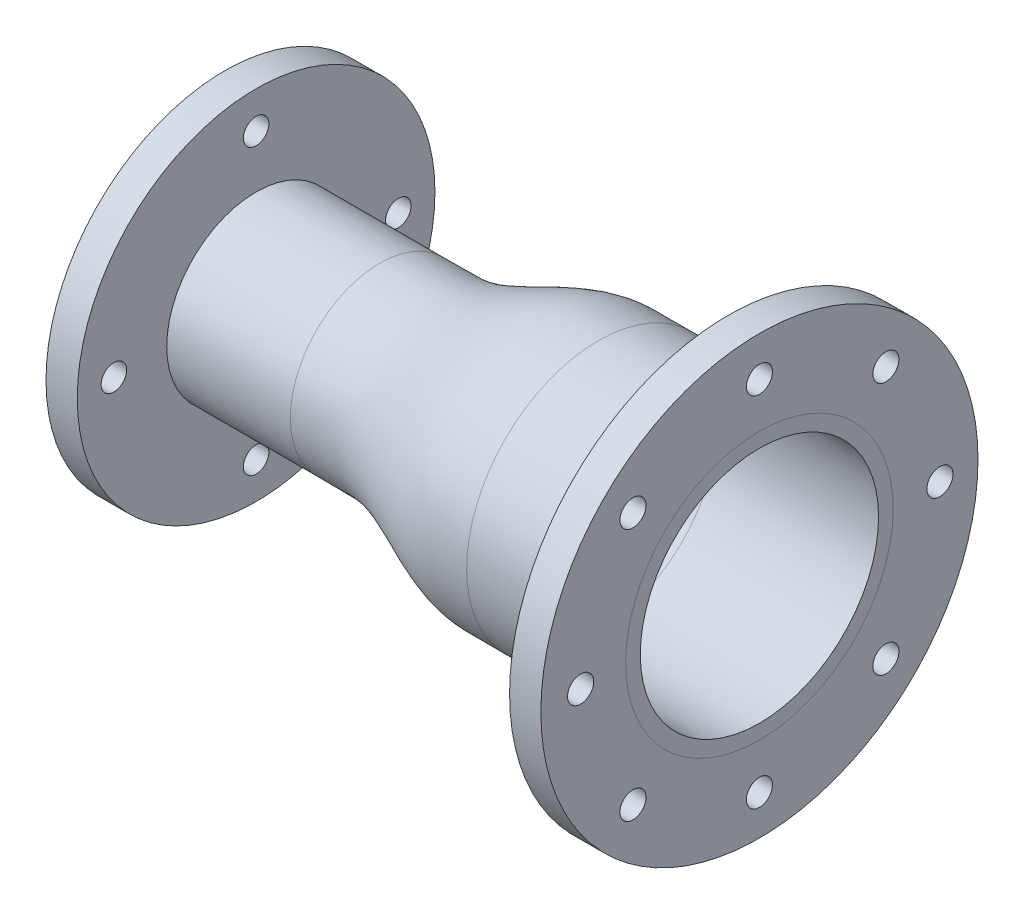
SolidWorks part; units mm, degrees
material "Cast Alloy Steel"
ref_plane "Front Plane" through (0, 0, 0) normal (0, 0, 1) x (1, 0, 0)
ref_plane "Top Plane" through (0, 0, 0) normal (0, 1, 0) x (1, 0, 0)
ref_plane "Right Plane" through (0, 0, 0) normal (1, 0, 0) x (0, 0, -1)
other "Configuration Table"
sketch "Sketch2" plane through (0, 0, 0) normal (0, 0, 1) x (1, 0, 0)
  line L0 (341.7, 0) -> (0, 0) construction
  line L4 (341.7, 76.1375) -> (341.7, 139.7)
  line L5 (20, 114.3) -> (0, 114.3)
  line L6 (341.7, 139.7) -> (321.7, 139.7)
  line L8 (0, 114.3) -> (0, 49.15)
  line L9 (321.7, 139.7) -> (321.7, 84.1375)
  line L10 (20, 114.3) -> (20, 57.15)
  line L11 (99, 57.15) -> (20, 57.15)
  line L12 (238.7, 76.1375) -> (321.7, 76.1375) construction
  line L13 (238.7, 84.1375) -> (321.7, 84.1375)
  line L14 (238.7, 76.1375) -> (341.7, 76.1375)
  line L15 (99, 49.15) -> (0, 49.15)
  line L16 (99, 49.15) -> (20, 49.15) construction
  spline S1 degree 3 poles (238.7, 84.1375) (238.3559, 84.1375) (237.6678, 84.1375) (236.4389, 84.1375) (234.866, 84.1375) (233.0965, 84.1375) (231.1795, 84.1375) (229.4099, 84.1375) (227.493, 84.1375) (225.7234, 84.1375) (223.8064, 84.1375) (222.0369, 84.1375) (220.1199, 84.1374) (218.3504, 84.1379) (216.4362, 84.1363) (214.6713, 84.1428) (212.7611, 84.0867) (210.998, 83.9819) (209.0881, 83.8116) (207.3251, 83.6037) (205.4153, 83.3256) (203.6525, 83.0215) (201.743, 82.6431) (199.9803, 82.2501) (198.071, 81.7796) (196.3085, 81.3056) (194.3993, 80.7519) (192.637, 80.2054) (190.7279, 79.5779) (188.9657, 78.9679) (187.0568, 78.2765) (185.2947, 77.6123) (183.3858, 76.8675) (181.6238, 76.159) (179.715, 75.3717) (177.9531, 74.629) (176.0443, 73.8103) (174.2824, 73.0438) (172.3737, 72.2052) (170.6119, 71.4256) (168.7018, 70.578) (166.9374, 69.795) (165.0248, 68.9495) (163.2593, 68.1744) (161.3467, 67.3439) (159.5811, 66.588) (157.6684, 65.784) (155.9029, 65.0579) (153.9901, 64.2918) (152.2245, 63.6059) (150.3116, 62.8888) (148.5459, 62.253) (146.6329, 61.5955) (144.8671, 61.0196) (142.954, 60.432) (141.188, 59.9252) (139.2748, 59.4172) (137.5086, 58.9881) (135.5952, 58.5689) (133.8288, 58.2258) (131.9153, 57.9039) (130.1487, 57.6544) (128.235, 57.4377) (126.4683, 57.2886) (124.7896, 57.1975) (123.4438, 57.157) (122.4205, 57.149) (121.678, 57.1501) (120.6018, 57.1498) (119.2022, 57.15) (117.2852, 57.15) (115.5156, 57.15) (113.5986, 57.15) (111.8291, 57.15) (109.9121, 57.15) (108.1426, 57.15) (106.2256, 57.15) (104.4561, 57.15) (102.5391, 57.15) (101.0399, 57.15) (99.811, 57.15) (99.2703, 57.15) (99, 57.15) knots 0 0 0 0 0.007154 0.014308 0.025551 0.039859 0.051101 0.06541 0.076652 0.09096 0.102202 0.116511 0.127753 0.142061 0.153304 0.167554 0.178755 0.193031 0.204272 0.218621 0.229935 0.244395 0.25581 0.270409 0.28194 0.296695 0.308353 0.323271 0.335057 0.350135 0.362043 0.377271 0.389288 0.404646 0.416757 0.43222 0.444402 0.459941 0.47217 0.487751 0.5 0.515621 0.527887 0.54348 0.555711 0.571243 0.583412 0.598851 0.610936 0.626254 0.638235 0.65341 0.665273 0.680292 0.692028 0.706883 0.718491 0.733185 0.74467 0.759216 0.770593 0.785014 0.796305 0.810635 0.821871 0.831257 0.838628 0.843146 0.846696 0.861005 0.872247 0.886555 0.897798 0.912106 0.923348 0.937657 0.948899 0.963207 0.974449 0.988758 0.994379 1 1 1 1 weights 0.576132 0.576132 0.576132 0.576132 0.576132 0.576132 0.576132 0.576132 0.576132 0.576132 0.576132 0.576132 0.576132 0.576132 0.576132 0.576132 0.576132 0.576132 0.576132 0.576132 0.576132 0.576132 0.576132 0.576132 0.576132 0.576132 0.576132 0.576132 0.576132 0.576132 0.576132 0.576132 0.576132 0.576132 0.576132 0.576132 0.576132 0.576132 0.576132 0.576132 0.576132 0.576132 0.576132 0.576132 0.576132 0.576132 0.576132 0.576132 0.576132 0.576132 0.576132 0.576132 0.576132 0.576132 0.576132 0.576132 0.576132 0.576132 0.576132 0.576132 0.576132 0.576132 0.576132 0.576132 0.576132 0.576132 0.576132 0.576132 0.576132 0.576132 0.576132 0.576132 0.576132 0.576132 0.576132 0.576132 0.576132 0.576132 0.576132 0.576132 0.576132 0.576132 0.576132
  spline S2 degree 1 poles (238.7, 76.1375) (99, 49.15) knots 0 0 1 1 construction
  spline S3 degree 3 poles (238.7, 76.1375) (235.6941, 76.1375) (231.1852, 76.1375) (225.925, 76.1375) (222.9189, 76.1376) (220.6647, 76.1373) (218.7847, 76.138) (217.2906, 76.1368) (216.1285, 76.1382) (215.0669, 76.1389) (213.7925, 76.1189) (211.4967, 76.0157) (208.2293, 75.6894) (204.2706, 75.0272) (200.2987, 74.1207) (194.9854, 72.6231) (188.3215, 70.2833) (180.2754, 66.9614) (172.1262, 63.3455) (163.7903, 59.6453) (155.1646, 56.0793) (147.6413, 53.4297) (141.3789, 51.6621) (136.5564, 50.5598) (131.6159, 49.7302) (127.4038, 49.3093) (124.4378, 49.1746) (122.9302, 49.1514) (122.1007, 49.1494) (121.357, 49.1504) (120.4173, 49.1498) (118.9131, 49.1501) (117.0359, 49.15) (114.7809, 49.15) (111.7752, 49.15) (106.5147, 49.15) (102.0059, 49.15) (99, 49.15) knots 0 0 0 0 0.0625 0.09375 0.109375 0.125 0.140625 0.148438 0.15625 0.164062 0.171875 0.1875 0.21875 0.25 0.28125 0.3125 0.375 0.4375 0.5 0.5625 0.625 0.6875 0.71875 0.75 0.78125 0.8125 0.828125 0.835938 0.839844 0.84375 0.851562 0.859375 0.875 0.890625 0.90625 0.9375 1 1 1 1
  dimension "D1" = 20
  dimension "D2" = 8
revolve "Revolve1" add sketch "Sketch2" angle 360 about L0
sketch "Sketch3" plane through (341.7, 0, 0) normal (1, 0, 0) x (0, 0, -1)
  circle A0 centre (0, -120.65) radius 11.175
  circle A1 centre (0, 0) radius 120.65 construction
  dimension "D1" = 22.35
  dimension "D2" = 241.3
extrude "Cut-Extrude1" [suppressed] cut sketch "Sketch3" against normal up to surface (20 mm away)
sketch "Sketch4" plane through (0, 0, 0) normal (-1, 0, 0) x (0, 0, 1)
  circle A0 centre (0, 0) radius 95.25 construction
  circle A1 centre (0, 95.25) radius 9.5
  dimension "D1" = 190.5
  dimension "D2" = 19
extrude "Cut-Extrude2" [suppressed] cut sketch "Sketch4" against normal up to surface (20 mm away)
pattern_circular "CirPattern1" [suppressed] count 4 over 360 about axis through (341.7, 0, 0) along (-1, 0, 0)
sketch "Sketch5" plane through (341.7, 0, 0) normal (1, 0, 0) x (0, 0, -1)
  circle A0 centre (0, 0) radius 85.5
  dimension "D1" = 171
split line "Split Line1"
hole_wizard "CSK for 5/8 Flat Head Machine Screw (100)1" positions "Sketch10" profile "Sketch11" countersink size "5/8" standard "Ansi Inch"
sketch "Sketch10" plane through (321.7, -86.9453, 61.2299) normal (-1, 0, 0) x (0, 0, 1)
  line L0 (-61.2299, 86.9453) -> (-61.2299, 353.2126) construction
  line L1 (-61.2299, 86.9453) -> (208.6165, 86.9453) construction
  line L2 (-61.2299, 86.9453) -> (-335.3638, 86.9453) construction
  line L3 (-61.2299, 86.9453) -> (-61.2299, -193.2291) construction
  line L7 (-61.2299, 86.9453) -> (113.4341, 261.6093) construction
  line L8 (-61.2299, 86.9453) -> (150.6399, -124.9245) construction
  line L9 (-61.2299, 86.9453) -> (-186.2909, 212.0063) construction
  line L10 (-61.2299, 86.9453) -> (-176.5965, -28.4213) construction
  circle A0 centre (-61.2299, 86.9453) radius 114.3 construction
  point P0 (-61.2299, 201.2453)
  point P1 (-176.5965, 86.9453)
  point P2 (-142.0522, 167.7676)
  point P3 (19.5924, 167.7676)
  point P4 (53.0701, 86.9453)
  point P5 (19.5924, 6.123)
  point P6 (-61.2299, -27.4065)
  point P7 (-142.0522, 6.123)
sketch "Sketch11" plane through (321.7, 114.3, 0) normal (0, 1, 0) x (0, 0, 1)
  line L0 (0, 0) -> (0, 20)
  line L1 (0, 20) -> (8.3337, 20)
  line L2 (8.3337, 20) -> (8.3337, 6.5623)
  line L3 (8.3337, 6.5623) -> (16.1544, 0)
  line L5 (16.1544, 0) -> (0, 0)
  line L6 (-8.3337, 6.5623) -> (-16.1544, 0) construction
  line L11 (0, -6.35) -> (0, 107.95) construction
  dimension "Thru Hole Dia." = 16.6675
  dimension "Thru Hole Depth" = 20
  dimension "Near C'Sink Dia." = 32.3088
  dimension "Near C'Sink Angle" = 100
hole_wizard "CSK for 5/8 Flat Head Machine Screw (100)2" [suppressed] positions "Sketch12" profile "Sketch13" countersink size "5/8" standard "Ansi Inch"
sketch "Sketch12" plane through (321.7, -86.9453, 61.2299) normal (-1, 0, 0) x (0, 0, 1)
  point P0 (-64.3378, 197.2771)
  point P1 (39.851, 49.4978)
  point P2 (-73.6499, -26.8437)
  point P3 (-171.7422, 70.605)
sketch "Sketch13" plane through (321.7, 110.3318, -3.1079) normal (0, 1, 0) x (0, 0, 1)
  line L0 (0, 0) -> (0, 20)
  line L1 (0, 20) -> (8.3337, 20)
  line L2 (8.3337, 20) -> (8.3337, 6.5623)
  line L3 (8.3337, 6.5623) -> (16.1544, 0)
  line L4 (16.1544, 0) -> (0, 0)
  line L5 (-8.3337, 6.5623) -> (-16.1544, 0) construction
  line L6 (0, -6.35) -> (0, 107.95) construction
  dimension "Thru Hole Dia." = 16.6675
  dimension "Thru Hole Depth" = 20
  dimension "Near C'Sink Dia." = 32.3088
  dimension "Near C'Sink Angle" = 100
hole_wizard "5/8 Clearance Hole1" positions "Sketch18" profile "Sketch19" hole
sketch "Sketch18" plane through (0, -86.9453, 61.2299) normal (-1, 0, 0) x (0, 0, 1)
  line L0 (-61.2299, 86.9453) -> (160.2598, 86.9453) construction
  line L1 (-61.2299, 86.9453) -> (-61.2299, 296.6144) construction
  line L2 (-61.2299, 86.9453) -> (-291.9631, 86.9453) construction
  line L3 (-61.2299, 86.9453) -> (-61.2299, -121.1078) construction
  circle A0 centre (-61.2299, 86.9453) radius 90.9114 construction
  point P0 (-61.2299, 177.798)
  point P1 (29.6815, 86.9453)
  point P2 (-61.2299, -3.9661)
  point P3 (-152.1413, 86.9453)
sketch "Sketch19" plane through (0, 90.8528, 0) normal (0, 1, 0) x (0, 0, 1)
  line L0 (0, 0) -> (0, 20)
  line L1 (0, 20) -> (8.1356, 20)
  line L2 (8.1356, 20) -> (8.1356, 0)
  line L3 (8.1356, 0) -> (0, 0)
  line L4 (0, -6.35) -> (0, 107.95) construction
  dimension "Thru Hole Dia." = 16.2712
  dimension "Thru Hole Depth" = 20
